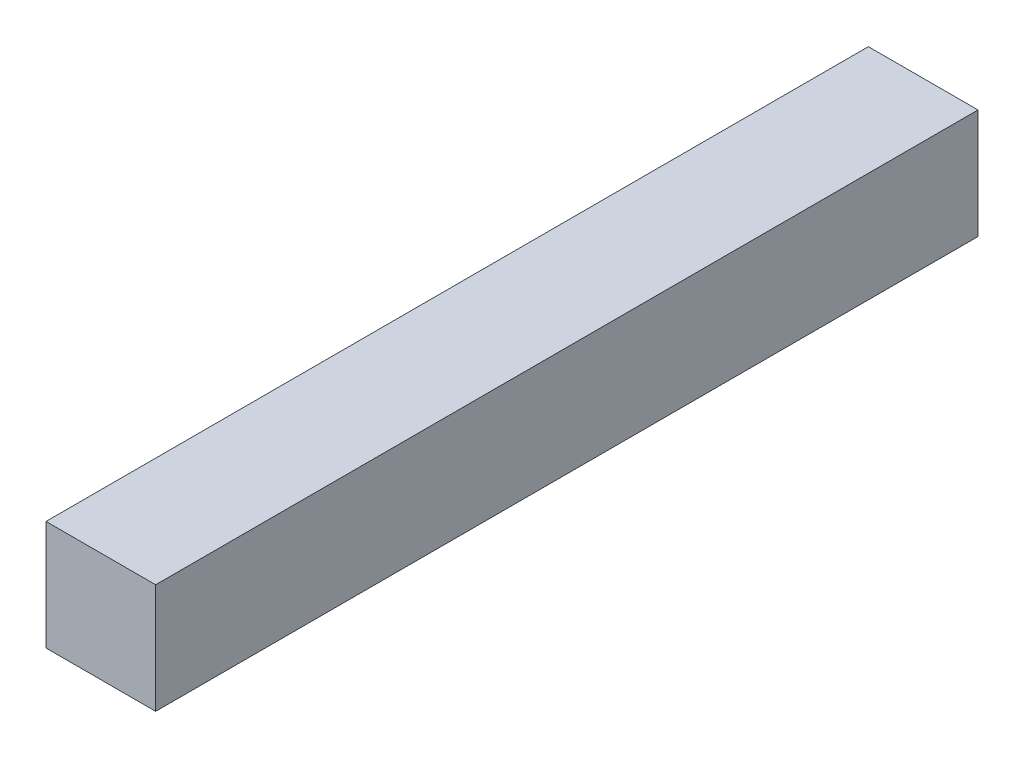
SolidWorks part; units mm, degrees
ref_plane "前基準面" through (0, 0, 0) normal (0, 0, 1) x (1, 0, 0)
ref_plane "上基準面" through (0, 0, 0) normal (0, 1, 0) x (1, 0, 0)
ref_plane "右基準面" through (0, 0, 0) normal (1, 0, 0) x (0, 0, -1)
sketch "草圖1" plane through (0, 0, 0) normal (0, 0, 1) x (1, 0, 0)
  line L1 (-2, 2) -> (2, 2)
  line L2 (-2, 2) -> (-2, -2)
  line L3 (-2, -2) -> (2, -2)
  line L4 (2, 2) -> (2, -2)
  line L5 (-2, 2) -> (2, -2) construction
  line L6 (-2, -2) -> (2, 2) construction
  point P0 (0, 0)
extrude "填料-伸長1" add sketch "草圖1" along normal blind 30 contours L3 L4 L1 L2
